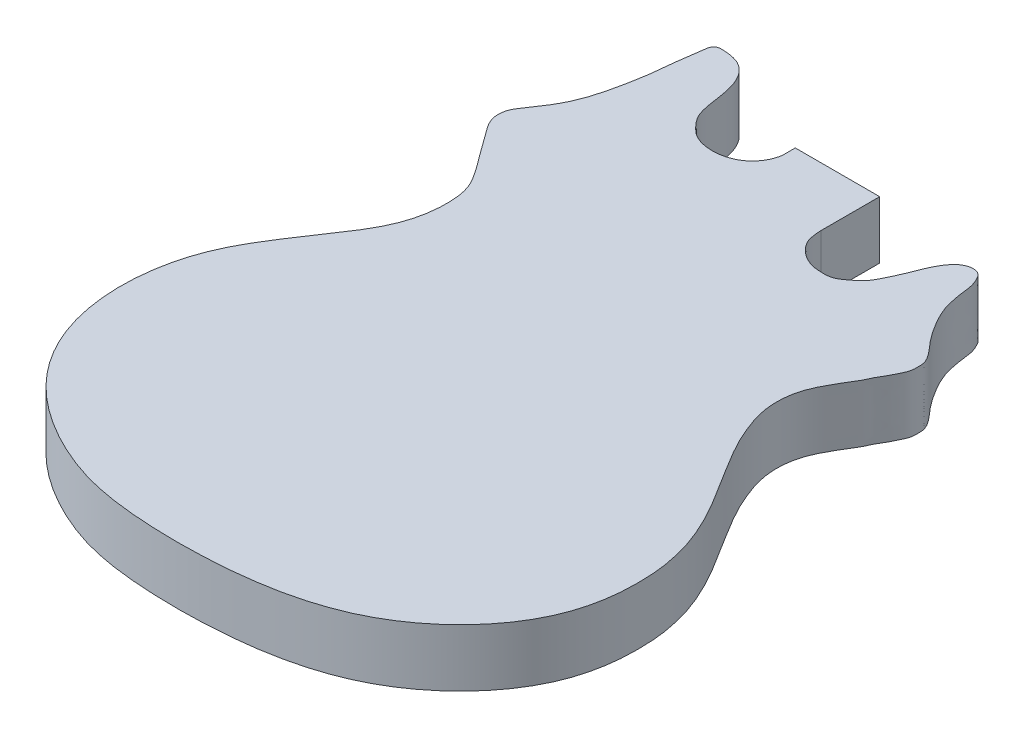
SolidWorks part; units mm, degrees
ref_plane "Front Plane" through (0, 0, 0) normal (0, 0, 1) x (1, 0, 0)
ref_plane "Top Plane" through (0, 0, 0) normal (0, 1, 0) x (1, 0, 0)
ref_plane "Right Plane" through (0, 0, 0) normal (1, 0, 0) x (0, 0, -1)
sketch "Sketch1" plane through (0, 0, 0) normal (0, 1, 0) x (1, 0, 0)
  line L0 (34, 148.5) -> (170, 148.5) construction
  line L1 (113.3333, 475) -> (566.6667, 475) construction
  line L2 (366.884, 629.0165) -> (366.884, 590.1968)
  line L3 (311.004, 621.7902) -> (311.004, 629.0165)
  line L4 (311.004, 629.0165) -> (366.884, 629.0165)
  spline S0 degree 2 poles (215.669, 336.647) (216.0314, 329.6639) (216.0303, 322.6761) knots 0 0 0 1 1 1
  spline S1 degree 3 poles (366.884, 590.1968) (366.884, 588.7219) (367.1954, 585.9161) (367.8584, 580.8687) (370.2183, 576.638) (373.656, 572.9139) (377.7436, 569.6464) (383.5739, 566.8986) (390.4513, 566.2582) (398.1526, 566.2615) (404.5886, 571.0337) (410.9497, 576.0837) (415.3218, 584.4013) (420.8686, 596.5228) (424.9577, 609.0356) (432.2646, 616.8784) (437.6931, 619.0937) (443.8512, 618.3519) (446.5156, 613.3114) (448.6424, 608.2037) (449.0636, 602.5748) (450.1117, 596.3504) (451.6808, 587.8622) (455.5119, 579.4319) (460.761, 570.7281) (465.7158, 563.473) (471.2252, 557.6254) (474.9603, 552.6443) (477.0415, 548.6468) (477.2321, 544.2856) (477.1796, 538.9007) (474.7855, 534.5304) (471.9712, 528.3967) (468.6167, 523.7961) (466.5381, 518.2752) (463.8413, 514.1641) (460.3003, 508.1001) (455.9078, 500.5313) (452.3912, 492.0928) (449.9815, 481.1301) (450.5699, 467.1894) (455.572, 453.1111) (460.7508, 441.535) (477.2922, 412.2459) (496.8647, 386.6957) (505.5974, 354.3232) (507.4936, 344.9949) (508.2845, 331.9773) (508.4129, 314.0273) (501.3882, 276.244) (472.8631, 240.162) (421.7779, 207.4086) (367.396, 198.2759) (311.2308, 198.2745) (272.0541, 202.8861) (232.1146, 218.257) (197.6429, 242.0538) (162.4161, 296.6298) (164.4777, 358.4599) (190.3043, 402.8255) (206.202, 426.429) (220.2891, 446.9924) (226.7609, 467.5059) (228.0552, 482.2801) (226.2683, 497.5063) (219.3538, 509.0937) (209.9389, 521.261) (201.5631, 533.3246) (192.4737, 545.1301) (193.6036, 555.883) (197.7923, 561.2399) (200.5946, 565.6062) (205.0034, 572.1229) (212.9516, 586.1943) (216.8455, 602.8064) (219.7659, 617.7812) (221.0158, 627.0552) (222.0203, 639.5165) (223.8848, 650.1357) (224.7871, 658.2165) (226.2919, 660.7497) (229.5206, 661.3692) (232.5235, 661.1328) (237.4425, 660.6729) (244.1718, 658.882) (253.7165, 649.5004) (256.4519, 635.1023) (258.0468, 622.7769) (260.5216, 614.5452) (265.1215, 608.8114) (271.5363, 602.4847) (280.7569, 599.6773) (291.631, 599.8424) (303.0224, 604.4935) (309.5059, 613.4697) (311.004, 619.7642) (311.004, 621.7902) knots 0 0 0 0 0.00316 0.005982 0.010803 0.013129 0.016778 0.021903 0.02655 0.031476 0.037806 0.042957 0.04871 0.057442 0.071592 0.076175 0.079681 0.083884 0.087866 0.09094 0.095781 0.099694 0.104434 0.114115 0.119169 0.126116 0.132777 0.136226 0.139412 0.142149 0.145426 0.150746 0.15245 0.159838 0.16272 0.16495 0.170281 0.177696 0.183572 0.189678 0.201496 0.212683 0.221325 0.228496 0.284386 0.287604 0.299888 0.304568 0.315372 0.338107 0.385165 0.407746 0.466775 0.498359 0.527971 0.54996 0.589189 0.614611 0.686418 0.703721 0.724062 0.747168 0.756238 0.769575 0.778552 0.788342 0.797787 0.811367 0.819933 0.82859 0.831653 0.834391 0.83964 0.848425 0.868653 0.875499 0.880975 0.888571 0.902141 0.903842 0.905977 0.907809 0.910449 0.912456 0.918334 0.924869 0.939758 0.948092 0.951603 0.957872 0.963487 0.970559 0.977642 0.986453 0.995699 1 1 1 1
extrude "Boss-Extrude1" add sketch "Sketch1" along normal blind 38.1
